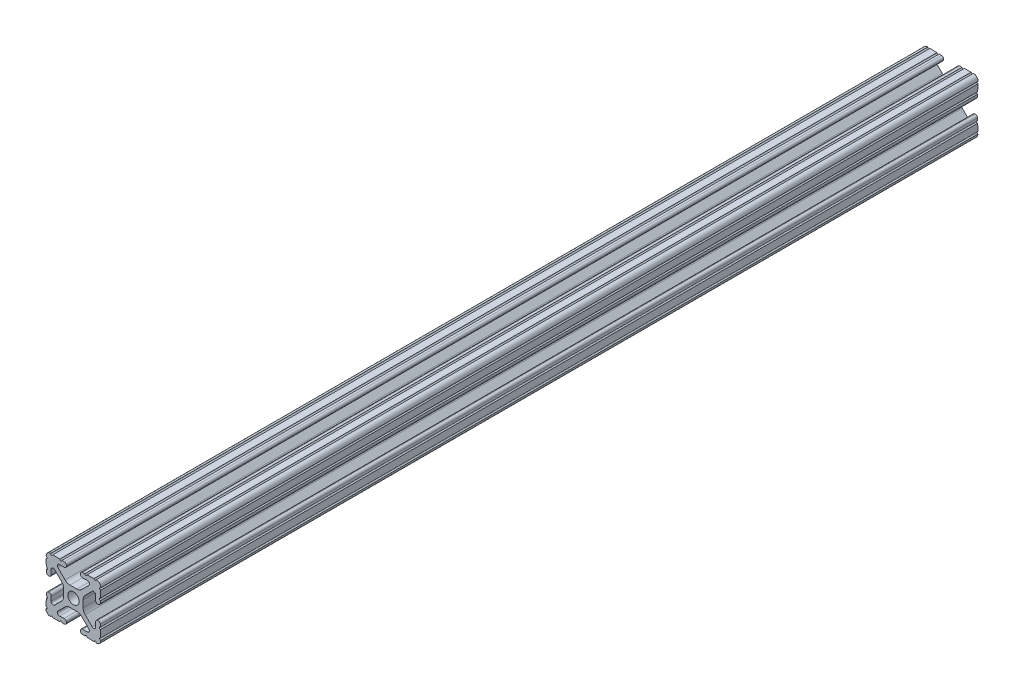
SolidWorks part; units mm, degrees
ref_plane "Front Plane" through (0, 0, 0) normal (0, 0, 1) x (1, 0, 0)
ref_plane "Top Plane" through (0, 0, 0) normal (0, 1, 0) x (1, 0, 0)
ref_plane "Right Plane" through (0, 0, 0) normal (1, 0, 0) x (0, 0, -1)
sketch "Sketch1" plane through (0, 0, 0) normal (0, 0, 1) x (1, 0, 0)
  line L0 (0, 0) -> (0, 12.7) construction
  line L1 (0, 0) -> (12.7, 0) construction
  line L2 (0, 0) -> (-12.7, 12.7) construction
  line L3 (-10.5971, 12.6988) -> (-4.2563, 12.4773)
  line L4 (-12.7, 12.7) -> (0, 12.7) construction
  line L6 (-4.3334, 10.2689) -> (-6.4194, 10.3417)
  line L10 (0, 4.4958) -> (-1.6181, 4.4958)
  line L11 (-3.8632, 5.4257) -> (-7.1345, 8.6971)
  line L24 (0, 0) -> (-12.7, 0) construction
  line L25 (-12.7, 0) -> (0, 0) construction
  line L26 (0, 0) -> (0, -12.7) construction
  line L27 (-12.7, -12.7) -> (-12.7, 12.7) construction
  line L28 (0, 12.7) -> (12.7, 12.7) construction
  line L29 (-3.2563, 11.2733) -> (-3.2518, 11.4002)
  line L30 (-12.7, -12.7) -> (12.7, -12.7) construction
  arc A0 (-12.1048, 12.1048) -> (-10.5971, 12.6988) centre (-10.668, 10.668) cw
  arc A5 (-4.2563, 12.4773) -> (-3.2518, 11.4002) centre (-4.2926, 11.4366) cw
  arc A6 (-1.6181, 4.4958) -> (-3.8632, 5.4257) centre (-1.6181, 7.6708) cw
  circle A16 centre (0, 0) radius 2.6035
  arc A18 (-7.1345, 8.6971) -> (-6.4194, 10.3417) centre (-6.453, 9.3786) cw
  circle A19 centre (-2.4696, 2.4696) radius 0.635 construction
  arc A20 (-3.2563, 11.2733) -> (-4.3334, 10.2689) centre (-4.297, 11.3096) cw
  circle A21 centre (-10.0585, 12.68) radius 0.508 construction
  circle A22 centre (-5.8193, 12.5319) radius 0.508 construction
  point P15 (0, 0)
  point P42 (-2.9332, 4.4958)
  point P80 (-12.7, 0)
  point P85 (0, -12.7)
  point P88 (0, -12.7)
  dimension "D11" = 2.032
  dimension "D15" = 3.175
  dimension "Center Hole Diameter" = 5.207
  dimension "D6" = 1.27
  dimension "D7" = 1.0414
  dimension "D13" = 1.016
  dimension "D1" = 45
  dimension "D2" = 2
  dimension "Rail Width" = 25.4
  dimension "D10" = 2.2098
  dimension "T-Slot Depth" = 8.2042
  dimension "D9" = 2.2098
  dimension "Rail Height" = 25.4
  dimension "D23" = 8.9916
  dimension "D5" = 14.8336
  dimension "D3" = 3.4925
  dimension "D4" = 5.8459
  dimension "T-Slot Width" = 6.5024
  dimension "D8" = 4.2418
  dimension "D12" = 2.6416
sketch "Sketch2" plane through (0, 0, 0) normal (1, 0, 0) x (0, 0, -1)
  line L0 (-203.2, 0) -> (203.2, 0)
  line L1 (-203.2, -12.7) -> (-203.2, 12.7)
  line L2 (0, 0) -> (0, 12.7) construction
  line L3 (0, 0) -> (0, 12.7) construction
  line L4 (203.2, -12.7) -> (203.2, 12.7)
  point P0 (-165.1, 0)
  point P3 (0, 0)
  point P7 (165.1, 0)
  point P11 (-203.2, 0)
  point P14 (203.2, 0)
  dimension "D1" = 38.1
  dimension "Representative Length" = 406.4
sketch "Sketch3" plane through (0, 0, 0) normal (0, 0, 1) x (1, 0, 0)
  line L0 (-3.2563, 11.2733) -> (-3.2518, 11.4002) construction
  line L1 (0, 0) -> (-12.7, 12.7) construction
  line L2 (0, 0) -> (-12.7, 12.7) construction
  line L3 (-4.4958, 0) -> (-2.6035, 0)
  line L4 (-4.4958, 0) -> (-4.4958, 1.6181)
  line L5 (-10.5971, 12.6988) -> (-4.2563, 12.4773) construction
  line L6 (-3.2563, 11.2733) -> (-3.2518, 11.4002)
  line L7 (-4.3334, 10.2689) -> (-6.4194, 10.3417) construction
  line L12 (-5.4257, 3.8632) -> (-8.6971, 7.1345)
  line L13 (-10.2689, 4.3334) -> (-10.3417, 6.4194)
  line L15 (-12.6988, 10.5971) -> (-12.4773, 4.2563)
  line L17 (-11.2733, 3.2563) -> (-11.4002, 3.2518)
  line L42 (-3.8632, 5.4257) -> (-7.1345, 8.6971) construction
  line L43 (0, 4.4958) -> (-1.6181, 4.4958) construction
  line L44 (-10.5971, 12.6988) -> (-4.2563, 12.4773)
  line L46 (-4.3334, 10.2689) -> (-6.4194, 10.3417)
  line L47 (-3.8632, 5.4257) -> (-7.1345, 8.6971)
  line L48 (0, 4.4958) -> (-1.6181, 4.4958)
  line L57 (0, 0) -> (-12.7, 0) construction
  line L59 (0, 4.4958) -> (0, 2.6035)
  arc A0 (-10.5971, 12.6988) -> (-12.1048, 12.1048) centre (-10.668, 10.668) ccw construction
  arc A1 (-3.2518, 11.4002) -> (-4.2563, 12.4773) centre (-4.2926, 11.4366) ccw construction
  circle A3 centre (0, 0) radius 2.6035
  arc A5 (-10.5971, 12.6988) -> (-12.6988, 10.5971) centre (-10.668, 10.668) ccw
  arc A6 (-5.4257, 3.8632) -> (-4.4958, 1.6181) centre (-7.6708, 1.6181) cw
  arc A7 (-10.3417, 6.4194) -> (-8.6971, 7.1345) centre (-9.3786, 6.453) cw
  arc A12 (-1.841, 1.841) -> (-2.6035, 0) centre (0, 0) ccw
  arc A14 (-4.3334, 10.2689) -> (-3.2563, 11.2733) centre (-4.297, 11.3096) ccw construction
  arc A15 (-4.3334, 10.2689) -> (-3.2563, 11.2733) centre (-4.297, 11.3096) ccw
  arc A16 (-3.2518, 11.4002) -> (-4.2563, 12.4773) centre (-4.2926, 11.4366) ccw
  arc A17 (-11.4002, 3.2518) -> (-12.4773, 4.2563) centre (-11.4366, 4.2926) cw
  arc A18 (-10.2689, 4.3334) -> (-11.2733, 3.2563) centre (-11.3096, 4.297) cw
  arc A35 (0, 2.6035) -> (-1.841, 1.841) centre (0, 0) ccw
  arc A38 (-6.4194, 10.3417) -> (-7.1345, 8.6971) centre (-6.453, 9.3786) ccw construction
  arc A39 (-3.8632, 5.4257) -> (-1.6181, 4.4958) centre (-1.6181, 7.6708) ccw construction
  arc A43 (-6.4194, 10.3417) -> (-7.1345, 8.6971) centre (-6.453, 9.3786) ccw
  arc A44 (-3.8632, 5.4257) -> (-1.6181, 4.4958) centre (-1.6181, 7.6708) ccw
  circle A51 centre (0, 0) radius 2.6035 construction
  dimension "D1" = 0
extrude "Boss-Extrude1" add sketch "Sketch3" along normal mid plane 406.4
sketch "Sketch4" plane through (0, 0, 0) normal (0, 0, 1) x (1, 0, 0)
  line L0 (0, 0) -> (-12.7, 12.7) construction
  line L1 (0, 0) -> (-12.7, 12.7) construction
  circle A0 centre (-5.8193, 12.5319) radius 0.508 construction
  circle A1 centre (-10.0585, 12.68) radius 0.508 construction
  circle A2 centre (-5.8193, 12.5319) radius 0.508
  circle A3 centre (-10.0585, 12.68) radius 0.508
  circle A4 centre (-12.68, 10.0585) radius 0.508
  circle A5 centre (-12.5319, 5.8193) radius 0.508
extrude "Cut-Extrude1" cut sketch "Sketch4" against normal through all both and the other way through all
pattern_circular "CirPattern1" count 4 over 360 about axis through (0, 0, 0) along (0, 0, 1) of "Boss-Extrude1", "Cut-Extrude1"
ref_plane "Contact Plane 1" through (0, 12.7, 0) normal (0, 1, 0) x (1, 0, 0)
ref_plane "Contact Plane 2" through (12.7, 0, 0) normal (1, 0, 0) x (0, 0, -1)
ref_plane "Contact Plane 3" through (0, -12.7, 0) normal (0, -1, 0) x (-1, 0, 0)
ref_plane "Contact Plane 4" through (-12.7, 0, 0) normal (-1, 0, 0) x (0, 0, 1)
equation "\"D1@Sketch2\"=\"Rail Width@Sketch1\"*1.5"
equation "\"D1@Boss-Extrude1\" = \"Representative Length@Sketch2\""
